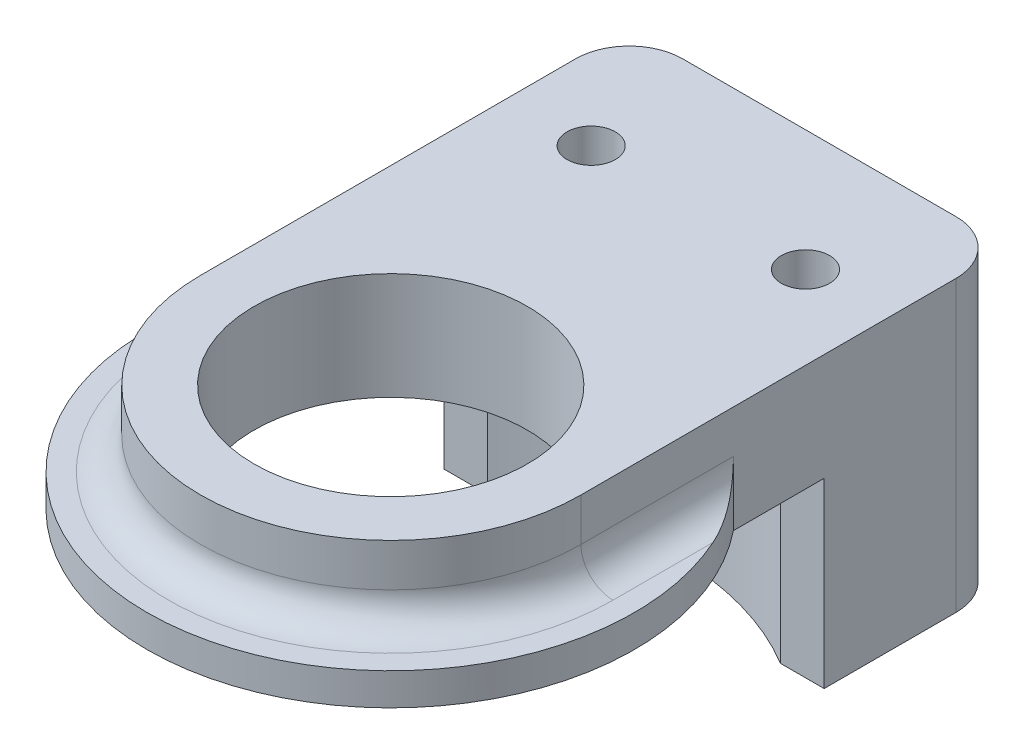
SolidWorks part; units mm, degrees
ref_plane "Front Plane" through (0, 0, 0) normal (0, 0, 1) x (1, 0, 0)
ref_plane "Top Plane" through (0, 0, 0) normal (0, 1, 0) x (1, 0, 0)
ref_plane "Right Plane" through (0, 0, 0) normal (1, 0, 0) x (0, 0, -1)
sketch "Sketch1" plane through (0, 0, 0) normal (0, 1, 0) x (1, 0, 0)
  circle A0 centre (0, 0) radius 22.75
  circle A1 centre (0, 0) radius 12.75
  dimension "D1" = 25.5
  dimension "D2" = 10
extrude "Boss-Extrude1" add sketch "Sketch1" along normal blind 3
sketch "Sketch2" plane through (0, 3, 0) normal (0, 1, 0) x (1, 0, 0)
  line L0 (0, 50.9728) -> (0, -56.8301) construction
  line L4 (17.75, 0) -> (17.75, 40)
  line L5 (17.75, 40) -> (-17.75, 40)
  line L6 (-17.75, 40) -> (-17.75, 0)
  circle A0 centre (0, 0) radius 12.75
  arc A1 (5, -17.0312) -> (17.75, 0) centre (0, 0) ccw
  circle A2 centre (0, 0) radius 12.75 construction
  arc A3 (-17.75, 0) -> (-5, -17.0312) centre (0, 0) ccw
  arc A4 (-5, -17.0312) -> (5, -17.0312) centre (0, 0) ccw
  dimension "D1" = 5
  dimension "D5" = 40
extrude "Boss-Extrude2" add sketch "Sketch2" along normal blind 7
sketch "Sketch3" plane through (0, 3, 0) normal (0, -1, 0) x (1, 0, 0)
  line L3 (17.75, -40) -> (17.75, -14.2302)
  line L4 (-17.75, -14.2302) -> (-17.75, -40)
  line L5 (-17.75, -40) -> (17.75, -40)
  line L6 (17.75, -40) -> (17.75, -14.2302)
  line L7 (-17.75, -14.2302) -> (-17.75, -40)
  line L8 (-17.75, -40) -> (17.75, -40)
  arc A1 (-17.75, -14.2302) -> (17.75, -14.2302) centre (0, 0) ccw
  arc A2 (-17.75, -14.2302) -> (17.75, -14.2302) centre (0, 0) ccw
  dimension "D1" = 0
extrude "Boss-Extrude3" add sketch "Sketch3" along normal up to surface (3 mm away) up to face at (0, 0, 22.75)
fillet "Fillet4" radius 5 2 edges at (17.75, 5, -40) (-17.75, 5, -40)
sketch "Sketch4" plane through (0, 10, 0) normal (0, 1, 0) x (1, 0, 0)
  line L0 (17.75, 28.7075) -> (-17.75, 28.7075) construction
  line L1 (17.75, 0) -> (17.75, 35) construction
  line L2 (-17.75, 35) -> (-17.75, 0) construction
  line L3 (12.75, 40) -> (-12.75, 40) construction
  circle A0 centre (10, 28.7075) radius 2.25
  circle A1 centre (-10, 28.7075) radius 2.25
  point P10 (0, 28.7075)
  dimension "D1" = 4.5
  dimension "D2" = 4.5
  dimension "D3" = 10
  dimension "D4" = 10
  dimension "D5" = 11.2925
extrude "Cut-Extrude1" cut sketch "Sketch4" against normal blind 15
sketch "Sketch5" plane through (0, 10, 0) normal (0, 1, 0) x (1, 0, 0)
  circle A0 centre (10, 28.7075) radius 3.5
  circle A1 centre (-10, 28.7075) radius 3.5
  dimension "D1" = 7
fillet "Fillet5" radius 3 3 edges at (-17.75, 3, -7.1151) (17.75, 3, -7.1151) (0, 3, 17.75)
sketch "Sketch6" plane through (0, 0, 0) normal (0, -1, 0) x (-1, 0, 0)
  line L0 (17.75, 22.7) -> (17.75, 35)
  line L1 (17.75, 35) -> (17.75, 14.2302) construction
  line L2 (12.75, 40) -> (-12.75, 40)
  line L3 (-17.75, 35) -> (-17.75, 22.7)
  line L4 (-17.75, 14.2302) -> (-17.75, 35) construction
  line L5 (-17.75, 22.7) -> (17.75, 22.7)
  arc A0 (17.75, 35) -> (12.75, 40) centre (12.75, 35) ccw
  arc A1 (-12.75, 40) -> (-17.75, 35) centre (-12.75, 35) ccw
  arc A2 (-12.75, 40) -> (-17.75, 35) centre (-12.75, 35) ccw construction
  circle A3 centre (10, 28.7075) radius 2.25
  circle A4 centre (-10, 28.7075) radius 2.25
  dimension "D1" = 17.3
extrude "Boss-Extrude4" add sketch "Sketch6" along normal blind 17
sketch "Sketch7" plane through (0, 0, 0) normal (0, -1, 0) x (-1, 0, 0)
  circle A0 centre (0, 0) radius 26.5
  dimension "D1" = 53
extrude "Cut-Extrude3" cut sketch "Sketch7" along normal blind 30
